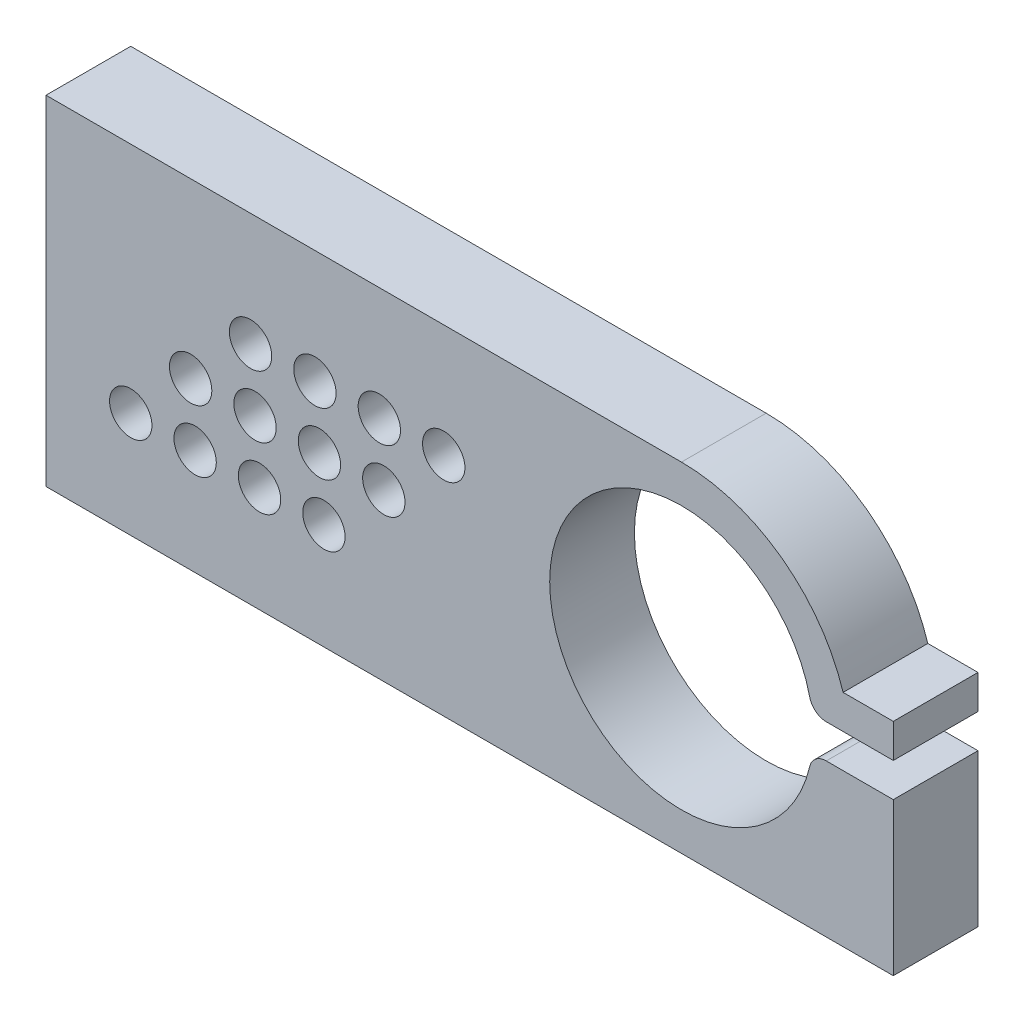
SolidWorks part; units mm, degrees
ref_plane "Front Plane" through (0, 0, 0) normal (0, 0, 1) x (1, 0, 0)
ref_plane "Top Plane" through (0, 0, 0) normal (0, 1, 0) x (1, 0, 0)
ref_plane "Right Plane" through (0, 0, 0) normal (1, 0, 0) x (0, 0, -1)
sketch "Sketch1" plane through (0, 0, 0) normal (0, 0, 1) x (1, 0, 0)
  line L0 (31.75, 0) -> (63.5, 0)
  line L1 (-63.5, -25.4) -> (63.5, -25.4)
  line L2 (-63.5, -25.4) -> (-63.5, 25.4)
  line L3 (-63.5, 25.4) -> (63.5, 25.4)
  line L4 (63.5, -25.4) -> (63.5, 25.4)
  line L5 (-63.5, -25.4) -> (63.5, 25.4) construction
  line L6 (-63.5, 25.4) -> (63.5, -25.4) construction
  line L7 (31.75, -2.54) -> (63.5, -2.54)
  line L8 (31.75, 2.54) -> (63.5, 2.54)
  line L9 (31.75, -2.54) -> (63.5, -2.54)
  line L10 (31.75, -7.62) -> (63.5, -7.62)
  line L11 (31.75, 7.62) -> (63.5, 7.62)
  line L12 (31.75, 2.54) -> (63.5, 2.54)
  circle A0 centre (31.75, 0) radius 19.75
  circle A1 centre (31.75, 0) radius 25.4
  point P0 (0, 0)
  dimension "D3" = 39.5
  dimension "D5" = 2.54
  dimension "D1" = 127
  dimension "D2" = 50.8
  dimension "D4" = 31.75
  dimension "D6" = 2.54
  dimension "D7" = 5.08
  dimension "D8" = 5.08
extrude "Boss-Extrude1" add sketch "Sketch1" along normal blind 12.7
fillet "Fillet2" radius 2.54 2 edges at (51.336, -2.54, 6.35) (51.336, 2.54, 6.35)
sketch "Sketch2" plane through (0, 0, 12.7) normal (0, 0, 1) x (1, 0, 0)
  line L0 (-63.5, -25.4) -> (-63.5, 25.4) construction
  line L1 (-63.5, -25.4) -> (63.5, -25.4) construction
  circle A0 centre (-50.8, -9.525) radius 3.175
  circle A3 centre (-41.8197, -0.5447) radius 3.175
  circle A4 centre (-32.8395, 8.4355) radius 3.175
  circle A5 centre (-41.148, -9.525) radius 3.175
  circle A6 centre (-32.1677, -0.5447) radius 3.175
  circle A7 centre (-23.1875, 8.4355) radius 3.175
  circle A8 centre (-31.496, -9.525) radius 3.175
  circle A9 centre (-22.5157, -0.5447) radius 3.175
  circle A10 centre (-13.5355, 8.4355) radius 3.175
  circle A11 centre (-21.844, -9.525) radius 3.175
  circle A12 centre (-12.8637, -0.5447) radius 3.175
  circle A13 centre (-3.8835, 8.4355) radius 3.175
  dimension "D1" = 6.35
  dimension "D2" = 12.7
  dimension "D4" = 15.875
  dimension "D3" = 3
extrude "Cut-Extrude1" cut sketch "Sketch2" against normal blind 12.7
